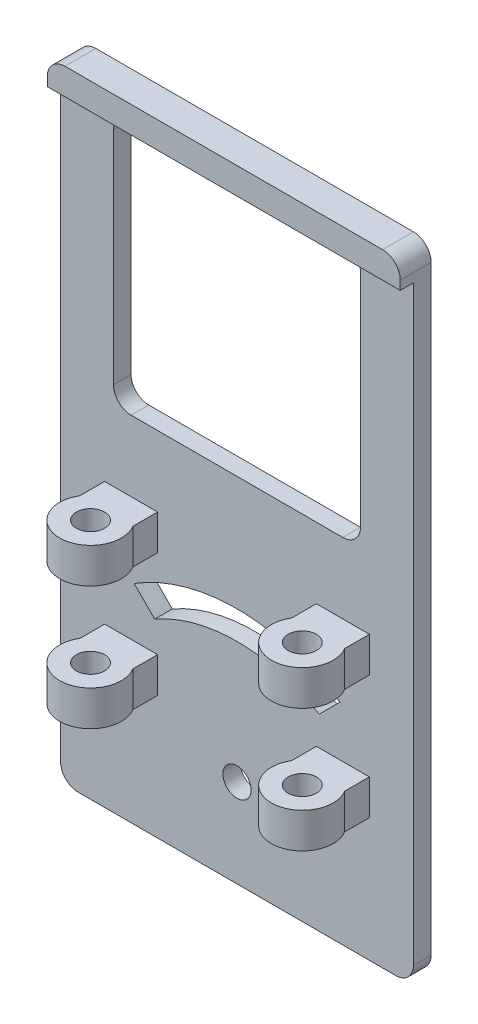
SolidWorks part; units mm, degrees
ref_plane "Front Plane" through (0, 0, 0) normal (0, 0, 1) x (1, 0, 0)
ref_plane "Top Plane" through (0, 0, 0) normal (0, 1, 0) x (1, 0, 0)
ref_plane "Right Plane" through (0, 0, 0) normal (1, 0, 0) x (0, 0, -1)
sketch "Sketch1" plane through (0, 0, 0) normal (0, 0, 1) x (1, 0, 0)
  line L1 (20, -20) -> (-20, -20)
  line L2 (20, -20) -> (20, 20)
  line L3 (20, 20) -> (-20, 20)
  line L4 (-20, -20) -> (-20, 20)
  line L5 (20, -20) -> (-20, 20) construction
  line L6 (20, 20) -> (-20, -20) construction
  point P0 (0, 0)
  dimension "D1" = 40
extrude "Boss-Extrude2" add sketch "Sketch1" along normal blind 2
sketch "Sketch2" plane through (0, 0, 2) normal (0, 0, 1) x (1, 0, 0)
  line L0 (-12, 0) -> (-12, 10) construction
  line L1 (0, 0) -> (-12, 0) construction
  line L2 (-15, 12) -> (-9, 12)
  line L3 (-15, 12) -> (-15, 8)
  line L4 (-15, 8) -> (-9, 8)
  line L5 (-9, 12) -> (-9, 8)
  line L6 (-15, 12) -> (-9, 8) construction
  line L7 (-15, 8) -> (-9, 12) construction
  point P1 (-12, 10)
  dimension "D1" = 10
  dimension "D2" = 4
  dimension "D3" = 6
  dimension "D4" = 12
extrude "Boss-Extrude5" add sketch "Sketch2" along normal blind 3
sketch "Sketch4" plane through (0, 12, 0) normal (0, 1, 0) x (1, 0, 0)
  line L1 (-9, -5) -> (-15, -5) construction
  circle A0 centre (-12, -6.6) radius 1.6
  circle A1 centre (-12, -6.6) radius 3.5
  point P9 (-12, -5)
  dimension "D1" = 3.2
  dimension "D2" = 7
  dimension "D3" = 1.6
extrude "Boss-Extrude6" add sketch "Sketch4" against normal blind 4
ref_plane "Plane2" through (0, 3, 0) normal (0, -1, 0) x (-1, 0, 0)
mirror "Mirror2" about plane through (0, 0, 0) normal (1, 0, 0) of "Boss-Extrude5", "Boss-Extrude6" second plane through (0, 3, 0) second plane normal (0, -1, 0)
sketch "Sketch6" plane through (0, 0, 2) normal (0, 0, 1) x (1, 0, 0)
  line L0 (-20, 20) -> (-15, 20)
  line L1 (20, 20) -> (-20, 20) construction
  line L2 (-15, 20) -> (-15, -20)
  line L3 (-20, -20) -> (20, -20) construction
  line L4 (-15, -20) -> (-20, -20)
  line L5 (-20, -20) -> (-20, 20)
  line L6 (20, 20) -> (15, 20)
  line L7 (15, 20) -> (15, -20)
  line L8 (15, -20) -> (20, -20)
  line L9 (20, -20) -> (20, 20)
  dimension "D1" = 5
  dimension "D2" = 5
  dimension "D4" = 5
extrude "Cut-Extrude1" [suppressed] cut sketch "Sketch6" against normal blind 3 contours L5 L0 L2 L4 | L9 L6 L7 L8
sketch "Sketch7" plane through (0, 0, 2) normal (0, 0, 1) x (1, 0, 0)
  line L0 (0, 0) -> (0, -15)
  line L1 (0, 0) -> (0, 7) construction
  line L2 (-8, 0) -> (8, 0) construction
  line L3 (9.3246, 1.3246) -> (11.6575, 3.6575)
  line L4 (-9.3246, 1.3246) -> (-11.6575, 3.6575)
  line L5 (-8, 0) -> (-9.3246, 1.3246) construction
  line L6 (8, 0) -> (9.3246, 1.3246) construction
  arc A0 (11.6575, 3.6575) -> (-11.6575, 3.6575) centre (0, -15) ccw
  arc A1 (9.3246, 1.3246) -> (-9.3246, 1.3246) centre (0, -15) ccw
  arc A2 (-9.3246, 1.3246) -> (9.3246, 1.3246) centre (0, -15) ccw construction
  arc A3 (-11.6575, 3.6575) -> (11.6575, 3.6575) centre (0, -15) ccw construction
  point P9 (0, 0)
  dimension "D1" = 15
  dimension "D2" = 7
  dimension "D3" = 3.2
  dimension "D4" = 8
  dimension "D5" = 45
  dimension "D6" = 45
extrude "Cut-Extrude2" cut sketch "Sketch7" against normal blind 2 contours A1 L3 A0 L4
sketch "Sketch8" plane through (0, 0, 0) normal (0, 0, -1) x (-1, 0, 0)
  line L0 (0, 0) -> (0, -10) construction
  circle A0 centre (0, -10) radius 1.6
  dimension "D1" = 10
  dimension "D2" = 3.2
extrude "Cut-Extrude3" cut sketch "Sketch8" against normal blind 2
sketch "Sketch18" plane through (0, 20, 0) normal (0, 1, 0) x (1, 0, 0)
  line L1 (20, -2) -> (14, -2)
  line L2 (20, -2) -> (20, 0)
  line L3 (20, 0) -> (14, 0)
  line L4 (20, 0) -> (-20, 0)
  line L5 (-20, 0) -> (-20, -2)
  line L6 (-20, -2) -> (20, -2)
  line L7 (20, -2) -> (20, 0)
  line L8 (20, 0) -> (-20, 0)
  line L9 (-20, 0) -> (-20, -2)
  line L10 (-20, -2) -> (20, -2)
  line L11 (20, -2) -> (20, 0)
  line L12 (14, -2) -> (14, 0)
  line L13 (-20, 0) -> (-14, 0)
  line L14 (-20, 0) -> (-20, -2)
  line L15 (-20, -2) -> (-14, -2)
  line L16 (-14, 0) -> (-14, -2)
  line M5 (20, 0) -> (-20, 0)
  line M6 (-20, 0) -> (-20, -2)
  line M7 (-20, -2) -> (20, -2)
  line M8 (20, -2) -> (20, 0)
  dimension "D2" = 6
  dimension "D3" = 6
  dimension "D1" = 0
extrude "Boss-Extrude10" add sketch "Sketch18" along normal blind 32 contours L12 M7 M8 M5 | L16 L8 M6 M7
sketch "Sketch19" plane through (0, 52, 0) normal (0, 1, 0) x (1, 0, 0)
  line L1 (-20, 0) -> (20, 0)
  line L2 (-20, 0) -> (-20, -3.5)
  line L3 (-20, -3.5) -> (20, -3.5)
  line L4 (-14, -2) -> (-14, 0)
  line L5 (-14, 0) -> (-20, 0)
  line L6 (-20, 0) -> (-20, -2)
  line L7 (-20, -2) -> (-14, -2)
  line L8 (-14, -2) -> (-14, 0)
  line L9 (-14, 0) -> (-20, 0)
  line L10 (-20, 0) -> (-20, -2)
  line L11 (-20, -2) -> (-14, -2)
  line L12 (20, 0) -> (20, -3.5)
  line M9 (-14, -2) -> (-14, 0)
  line M10 (-14, 0) -> (-20, 0)
  line M11 (-20, 0) -> (-20, -2)
  line M12 (-20, -2) -> (-14, -2)
  dimension "D2" = 3.5
  dimension "D3" = 40
  dimension "D1" = 0
extrude "Boss-Extrude11" add sketch "Sketch19" against normal blind 3 contours L12 L1 L2 L3 M9 M12 | M12 M9 M10 M11
fillet "Fillet1" radius 2 8 edges at (20, -20, 1) (-20, -20, 1) (20, 52, 1.75) (-20, 52, 1.75) (14, 20, 1) (-14, 20, 1) (-14, 49, 1) (14, 49, 1)
